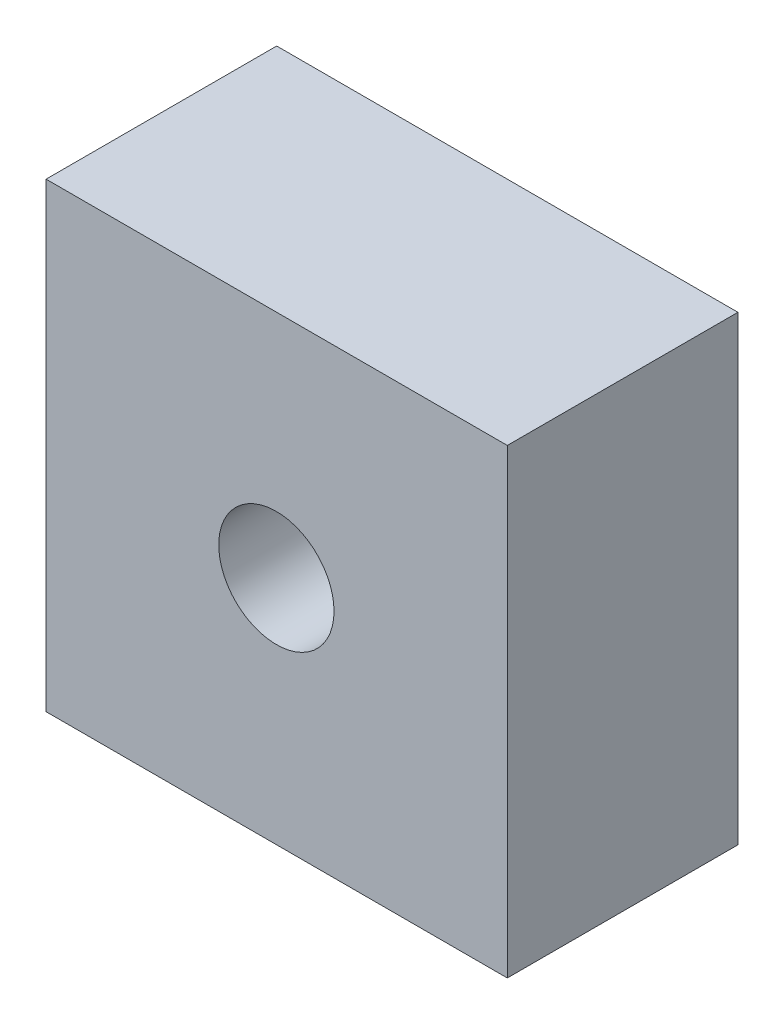
SolidWorks part; units mm, degrees
ref_plane "前视基准面" through (0, 0, 0) normal (0, 0, 1) x (1, 0, 0)
ref_plane "上视基准面" through (0, 0, 0) normal (0, 1, 0) x (1, 0, 0)
ref_plane "右视基准面" through (0, 0, 0) normal (1, 0, 0) x (0, 0, -1)
other "Configuration Table"
sketch "草图1" plane through (0, 0, 0) normal (0, 0, 1) x (1, 0, 0)
  line L1 (0, 0) -> (20, 0)
  line L2 (0, 0) -> (0, 20)
  line L3 (0, 20) -> (20, 20)
  line L4 (20, 0) -> (20, 20)
extrude "BaseBox" add sketch "草图1" along normal blind 10
hole_wizard "孔1" positions "草图3" profile "草图2" legacy
sketch "草图3" plane through (0, 0, 10) normal (0, 0, 1) x (1, 0, 0)
  point P0 (9.9865, 10.0143)
sketch "草图2" plane through (9.9865, 10.0143, 10) normal (1, 0, 0) x (0, -1, 0)
  line L0 (0, 0) -> (0, 10)
  line L1 (0, 10) -> (2.5, 10)
  line L2 (2.5, 10) -> (2.5, 0)
  line L3 (2.5, 0) -> (0, 0)
  line L4 (0, 110) -> (0, -10) construction
  dimension "直径" = 5
  dimension "深度" = 10
